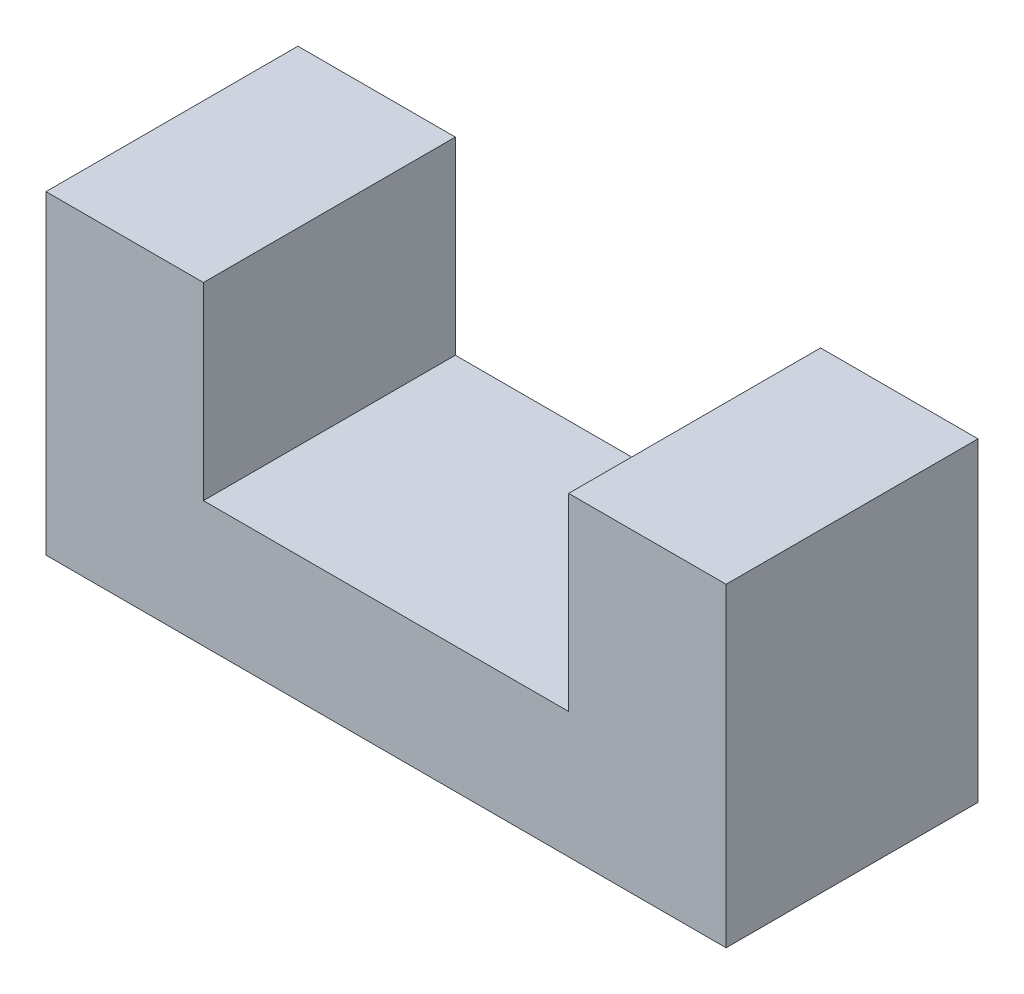
SolidWorks part; units mm, degrees
ref_plane "Plan de face" through (0, 0, 0) normal (0, 0, 1) x (1, 0, 0)
ref_plane "Plan de dessus" through (0, 0, 0) normal (0, 1, 0) x (1, 0, 0)
ref_plane "Plan de droite" through (0, 0, 0) normal (1, 0, 0) x (0, 0, -1)
sketch "Esquisse1" plane through (0, 0, 0) normal (0, 0, 1) x (1, 0, 0)
  line L0 (-2.9, 3) -> (-2.9, 0)
  line L1 (-2.9, 0) -> (2.9, 0)
  line L2 (-2.9, 3) -> (-5.4, 3)
  line L3 (-5.4, 3) -> (-5.4, -2)
  line L4 (-5.4, -2) -> (5.4, -2)
  line L5 (0, -2) -> (0, 0)
  line L6 (5.4, 3) -> (5.4, -2)
  line L7 (2.9, 3) -> (5.4, 3)
  line L8 (2.9, 3) -> (2.9, 0)
  point P11 (-2, 2.8443)
  dimension "D1" = 2.5
  dimension "D2" = 5
  dimension "D3" = 5.4
  dimension "D4" = 2
extrude "Boss.-Extru.1" add sketch "Esquisse1" along normal blind 4 contours L4 L5 L1 L0 L2 L3 | L7 L8 L1 L5 L4 L6
